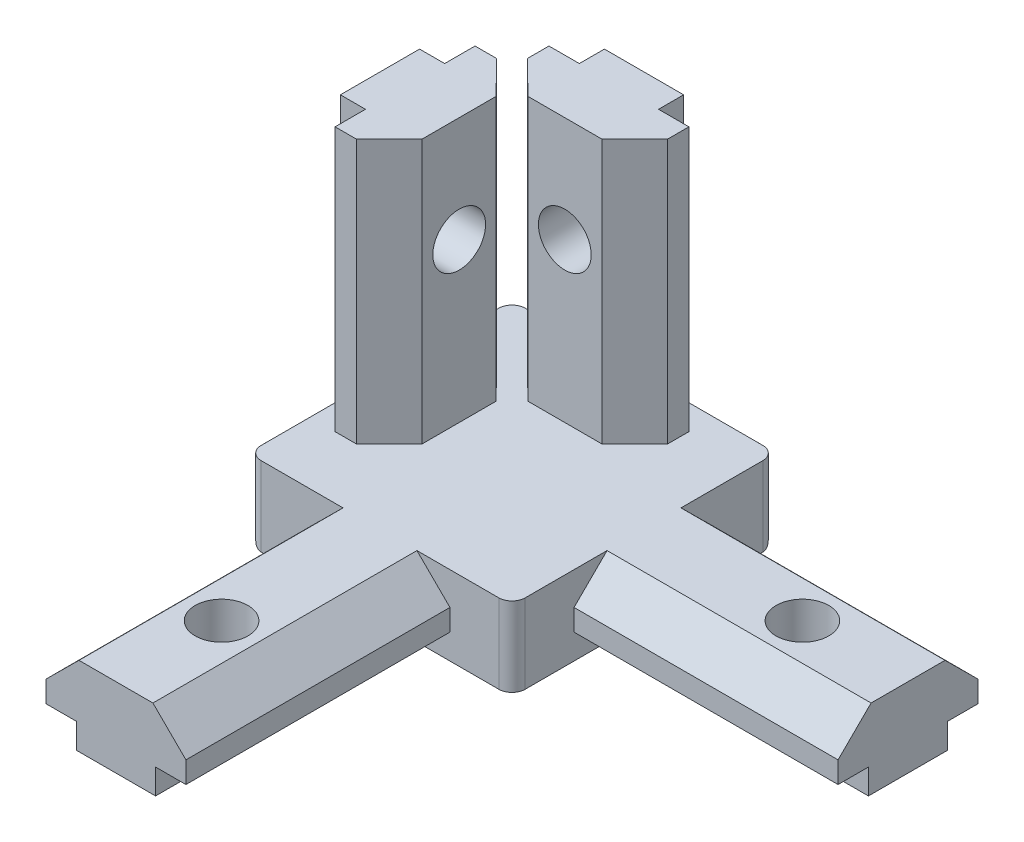
SolidWorks part; units mm, degrees
ref_plane "Front (XY)" through (0, 0, 0) normal (0, 0, 1) x (1, 0, 0)
ref_plane "Top (XZ)" through (0, 0, 0) normal (0, 1, 0) x (1, 0, 0)
ref_plane "Right (YZ)" through (0, 0, 0) normal (1, 0, 0) x (0, 0, -1)
sketch "Sketch1" plane through (0, 0, 0) normal (0, 1, 0) x (1, 0, 0)
  line L0 (-10, 10) -> (-10, -10)
  line L1 (-10, -10) -> (10, -10)
  line L2 (10, -10) -> (10, 10)
  line L3 (10, 10) -> (-10, 10)
  point P4 (0, 10)
  point P6 (10, 0)
  dimension "D1" = 20
  dimension "D2" = 20
extrude "Boss-Extrude1" add sketch "Sketch1" along normal blind 6
sketch "Sketch2" plane through (0, 0, 0) normal (0, 1, 0) x (1, 0, 0)
  line L0 (0, 0) -> (0, 10) construction
  line L1 (10, 10) -> (-10, 10) construction
  line L2 (-3, 10) -> (3, 10)
  line L3 (-3, 10) -> (-3, 8.1)
  line L4 (3, 10) -> (3, 8.1)
  line L5 (-3, 8.1) -> (-5.3, 8.1)
  line L6 (3, 8.1) -> (5.3, 8.1)
  line L7 (-5.3, 8.1) -> (-5.3, 6.48)
  line L8 (5.3, 8.1) -> (5.3, 6.48)
  line L9 (-2.8, 4) -> (2.8, 4)
  line L10 (-2.8, 4) -> (-5.3, 6.48)
  line L11 (2.8, 4) -> (5.3, 6.48)
  point P7 (0, 10)
  dimension "D1" = 6
  dimension "D2" = 1.9
  dimension "D3" = 2.3
  dimension "D4" = 1.62
  dimension "D5" = 5.6
  dimension "D6" = 6
extrude "Boss-Extrude2" add sketch "Sketch2" along normal blind 26
sketch "Sketch5" plane through (0, 0, -4) normal (0, 0, 1) x (1, 0, 0)
  line L0 (-2.8, 26) -> (2.8, 26) construction
  circle A0 centre (0, 18) radius 2
  dimension "D1" = 4
  dimension "D2" = 18
  dimension "D3" = 8
extrude "Cut-Extrude1" cut sketch "Sketch5" against normal through all
sketch "Sketch3" plane through (0, 0, 0) normal (0, 0, 1) x (1, 0, 0)
  line L0 (0, 0) -> (0, 10.6146) construction
pattern_circular "CirPattern1" count 2 over 90 about axis through (0, 0, 0) along (0, 1, 0) of "Boss-Extrude2", "Cut-Extrude1"
sketch "Sketch4" plane through (10, 6.0451, 0.4301) normal (1, 0, 0) x (0, 0, 1)
  line L0 (-0.4301, -1.9774) -> (-0.4301, 6.0451) construction
  line L2 (-3.4301, 6.0451) -> (2.5699, 6.0451)
  line L3 (-3.4301, 6.0451) -> (-3.4301, 4.1451)
  line L4 (2.5699, 6.0451) -> (2.5699, 4.1451)
  line L5 (-3.4301, 4.1451) -> (-5.7301, 4.1451)
  line L6 (2.5699, 4.1451) -> (4.8699, 4.1451)
  line L7 (-5.7301, 4.1451) -> (-5.7301, 2.5251)
  line L8 (4.8699, 4.1451) -> (4.8699, 2.5251)
  line L9 (-3.2301, 0.0451) -> (2.3699, 0.0451)
  line L10 (-3.2301, 0.0451) -> (-5.7301, 2.5251)
  line L11 (2.3699, 0.0451) -> (4.8699, 2.5251)
  line L12 (9.5699, 0.0451) -> (-10.4301, 0.0451) construction
  point P7 (-0.4301, 6.0451)
  point P16 (-0.4301, 0.0451)
  point P19 (-0.4301, 0.0451)
  dimension "D1" = 6
  dimension "D2" = 1.9
  dimension "D3" = 2.3
  dimension "D4" = 1.62
  dimension "D5" = 5.6
  dimension "D6" = 6
extrude "Boss-Extrude3" add sketch "Sketch4" along normal blind 20
sketch "Sketch6" plane through (0, 6, 0) normal (0, 1, 0) x (1, 0, 0)
  line L0 (30, 2.8) -> (30, -2.8) construction
  circle A0 centre (22, 0) radius 2
  dimension "D1" = 4
  dimension "D2" = 22
  dimension "D3" = 8
extrude "Cut-Extrude2" cut sketch "Sketch6" against normal through all
pattern_circular "CirPattern2" count 2 over 90 about axis through (0, 0, 0) along (0, 1, 0) of "Boss-Extrude3", "Cut-Extrude2"
fillet "Fillet1" radius 1 6 edges at (0, 0, -10) (-10, 0, 0) (-10, 3, 10) (-10, 3, -10) (10, 3, -10) (10, 3, 10)
